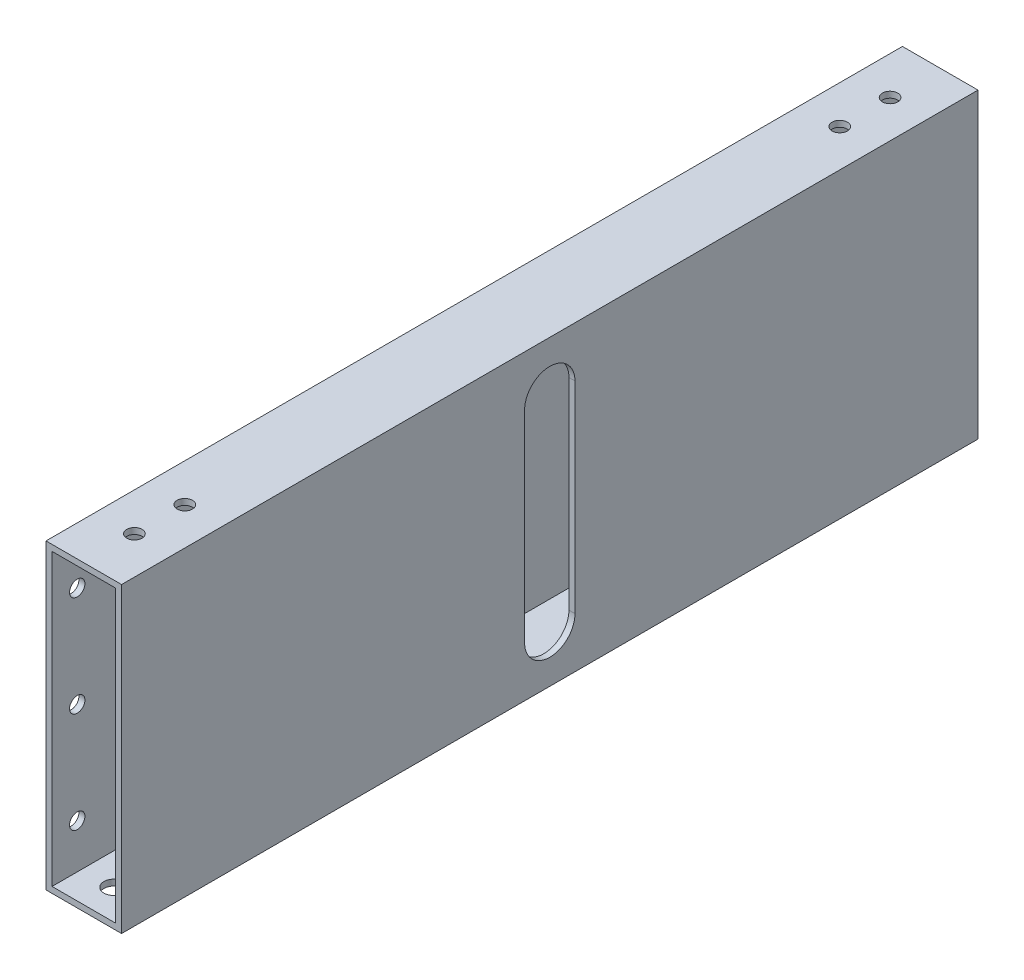
SolidWorks part; units mm, degrees
material "6063-T5"
ref_plane "前视基准面" through (0, 0, 0) normal (0, 0, 1) x (1, 0, 0)
ref_plane "上视基准面" through (0, 0, 0) normal (0, 1, 0) x (1, 0, 0)
ref_plane "右视基准面" through (0, 0, 0) normal (1, 0, 0) x (0, 0, -1)
sketch "草图1" plane through (0, 0, 0) normal (0, 0, 1) x (1, 0, 0)
  line L0 (-6.3, -28.8) -> (-6.3, 28.8)
  line L1 (-7.5, -30) -> (7.5, -30)
  line L2 (-7.5, -30) -> (-7.5, 30)
  line L3 (-7.5, 30) -> (7.5, 30)
  line L4 (7.5, -30) -> (7.5, 30)
  line L5 (0, 30) -> (0, -30) construction
  line L6 (-7.5, 0) -> (7.5, 0) construction
  line L7 (-6.3, 28.8) -> (6.3, 28.8)
  line L8 (6.3, -28.8) -> (6.3, 28.8)
  line L9 (-6.3, -28.8) -> (6.3, -28.8)
  point P0 (0, 0)
  dimension "D1" = 60
  dimension "D2" = 15
  dimension "D3" = 1.2
extrude "凸台-拉伸1" add sketch "草图1" along normal mid plane 170
sketch "草图2" plane through (0, -28.8, 0) normal (0, 1, 0) x (1, 0, 0)
  line L0 (0, -85) -> (0, -55) construction
  line L1 (7.5, -85) -> (-7.5, -85) construction
  line L2 (0, -70) -> (7.5, -70) construction
  line L3 (7.5, -85) -> (7.5, 85) construction
  circle A0 centre (0, -79) radius 2
  circle A1 centre (0, -61) radius 2
  dimension "D3" = 4
  dimension "D1" = 30
  dimension "D2" = 18
extrude "切除-拉伸1" cut sketch "草图2" against normal blind 10
mirror "镜向1" about plane through (0, 0, 0) normal (0, 0, 1) of "切除-拉伸1"
sketch "草图3" plane through (0, 30, 0) normal (0, 1, 0) x (1, 0, 0)
  line L0 (0, 0) -> (7.5, 0) construction
  line L1 (7.5, -85) -> (7.5, 85) construction
  arc A0 (-1.55, -65) -> (1.65, -65) centre (0.05, -65) ccw construction
  arc A1 (1.65, -75) -> (-1.55, -75) centre (0.05, -75) ccw construction
  arc A2 (-1.55, -65) -> (1.65, -65) centre (0.05, -65) ccw construction
  arc A3 (1.65, -75) -> (-1.55, -75) centre (0.05, -75) ccw construction
  circle A4 centre (0.05, -75) radius 1.525
  circle A5 centre (0.05, -65) radius 1.525
  arc A6 (1.65, 75) -> (-1.55, 75) centre (0.05, 75) cw construction
  arc A7 (-1.55, 65) -> (1.65, 65) centre (0.05, 65) cw construction
  circle A8 centre (0.05, 65) radius 1.525
  circle A9 centre (0.05, 75) radius 1.525
  dimension "D1" = 3.05
extrude "切除-拉伸2" cut sketch "草图3" against normal blind 10
sketch "草图4" plane through (-6.3, 0, 0) normal (1, 0, 0) x (0, 0, -1)
  line L0 (0, 0) -> (0, 49.1288) construction
  circle A0 centre (0, -20) radius 1.525 construction
  circle A1 centre (0, 0) radius 1.525 construction
  circle A2 centre (0, 20) radius 1.525 construction
  circle A3 centre (-80, -20) radius 1.525 construction
  circle A4 centre (-80, 0) radius 1.525 construction
  circle A5 centre (-80, 20) radius 1.525 construction
  circle A6 centre (0, -20) radius 1.525
  circle A7 centre (0, 0) radius 1.525
  circle A8 centre (0, 20) radius 1.525
  circle A9 centre (-80, -20) radius 1.525
  circle A10 centre (-80, 0) radius 1.525
  circle A11 centre (-80, 20) radius 1.525
  circle A12 centre (80, 20) radius 1.525
  circle A13 centre (80, 0) radius 1.525
  circle A14 centre (80, -20) radius 1.525
extrude "切除-拉伸3" cut sketch "草图4" against normal blind 10
sketch "草图5" plane through (7.5, 0, 0) normal (1, 0, 0) x (0, 0, -1)
  line L0 (0, -20) -> (0, 20) construction
  line L1 (-5, -20) -> (-5, 20)
  line L2 (5, -20) -> (5, 20)
  line L3 (-85, 30) -> (85, 30) construction
  arc A0 (-5, -20) -> (5, -20) centre (0, -20) ccw
  arc A1 (5, 20) -> (-5, 20) centre (0, 20) ccw
  point P2 (0, 0)
  dimension "D1" = 10
  dimension "D2" = 5
extrude "切除-拉伸4" cut sketch "草图5" against normal blind 10
